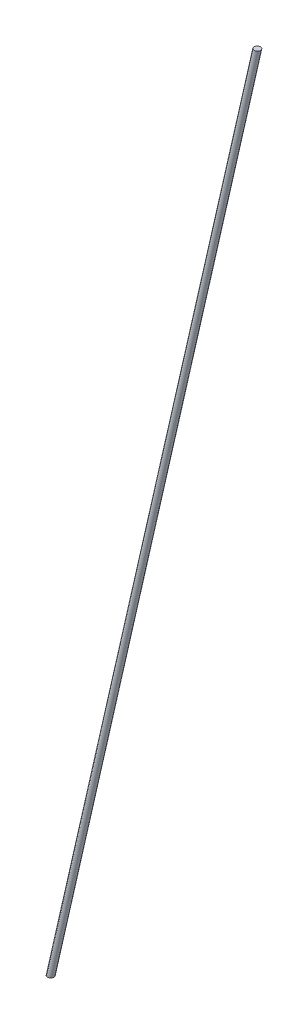
SolidWorks part; units mm, degrees
ref_plane "Front Plane" through (0, 0, 0) normal (0, 0, 1) x (1, 0, 0)
ref_plane "Top Plane" through (0, 0, 0) normal (0, 1, 0) x (1, 0, 0)
ref_plane "Right Plane" through (0, 0, 0) normal (1, 0, 0) x (0, 0, -1)
sketch "Sketch1" plane through (0, 0, 0) normal (0, 0, 1) x (1, 0, 0)
  line L0 (0, 0) -> (0, -570) construction
  line L1 (0, -570) -> (-130, -570) construction
  line L2 (-130, -570) -> (0, 0)
  dimension "D1" = 570
  dimension "D2" = 130
sketch "Sketch2" plane through (0, 0, 0) normal (0, 1, 0) x (1, 0, 0)
  circle A0 centre (0, 0) radius 2
  dimension "D1" = 4
sweep "Sweep1" add profiles "Sketch2" path "Sketch1"
